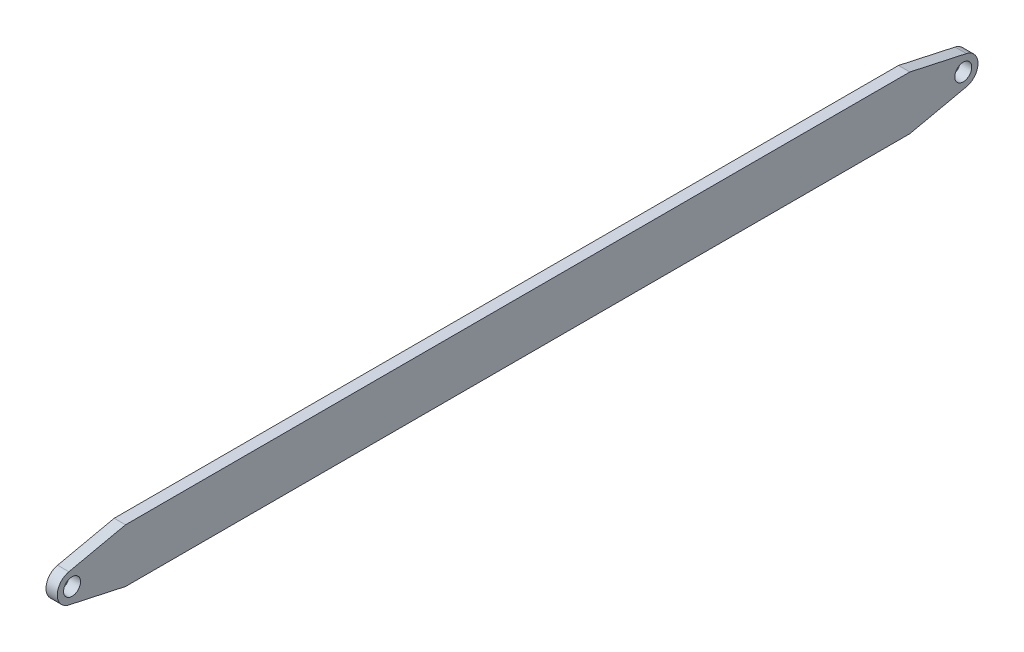
SolidWorks part; units mm, degrees
ref_plane "Front Plane" through (0, 0, 0) normal (0, 0, 1) x (1, 0, 0)
ref_plane "Top Plane" through (0, 0, 0) normal (0, 1, 0) x (1, 0, 0)
ref_plane "Right Plane" through (0, 0, 0) normal (1, 0, 0) x (0, 0, -1)
sketch "Sketch1" plane through (0, 0, 0) normal (1, 0, 0) x (0, 0, -1)
  line L0 (30, 15) -> (-1.7607, 8.0727)
  line L1 (30, 15) -> (470, 15)
  line L2 (30, 15) -> (30, -15) construction
  line L3 (30, -15) -> (470, -15)
  line L5 (30, -15) -> (-1.7607, -8.0727)
  line L6 (250, -15) -> (250, 15) construction
  line L7 (470, 15) -> (470, -15) construction
  line L10 (470, -15) -> (501.7607, -8.0727)
  line L11 (470, 15) -> (501.7607, 8.0727)
  circle A2 centre (0, 0) radius 4.7625
  arc A4 (-1.7607, 8.0727) -> (-1.7607, -8.0727) centre (0, 0) ccw
  arc A5 (-1.7607, -8.0727) -> (-1.7607, 8.0727) centre (0, 0) ccw construction
  arc A6 (501.7607, -8.0727) -> (501.7607, 8.0727) centre (500, 0) cw construction
  circle A7 centre (500, 0) radius 4.7625
  arc A8 (501.7607, 8.0727) -> (501.7607, -8.0727) centre (500, 0) cw
  point P0 (0, 0)
  point P13 (30, 0)
  dimension "D4" = 9.525
  dimension "D7" = 3.5
  dimension "D1" = 250
  dimension "D8" = 30
  dimension "D9" = 30
extrude "Boss-Extrude1" add sketch "Sketch1" along normal mid plane 6.35
